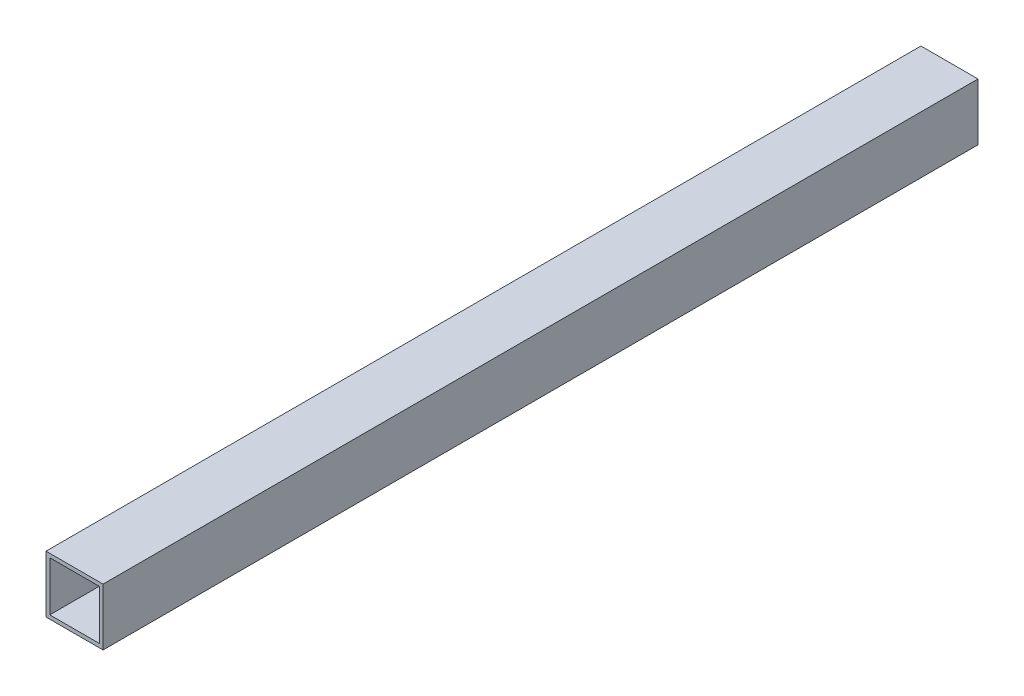
SolidWorks part; units mm, degrees
material "Aleación 1060"
ref_plane "Alzado" through (0, 0, 0) normal (0, 0, 1) x (1, 0, 0)
ref_plane "Planta" through (0, 0, 0) normal (0, 1, 0) x (1, 0, 0)
ref_plane "Vista lateral" through (0, 0, 0) normal (1, 0, 0) x (0, 0, -1)
sketch "Croquis1" plane through (0, 0, 0) normal (0, 0, 1) x (1, 0, 0)
  line L1 (15, -15) -> (-15, -15)
  line L2 (15, -15) -> (15, 15)
  line L3 (15, 15) -> (-15, 15)
  line L4 (-15, -15) -> (-15, 15)
  line L5 (15, -15) -> (-15, 15) construction
  line L6 (15, 15) -> (-15, -15) construction
  point P0 (0, 0)
  dimension "D1" = 30
  dimension "D2" = 30
extrude "Extruir-Lámina1" add sketch "Croquis1" along normal blind 460 thin
